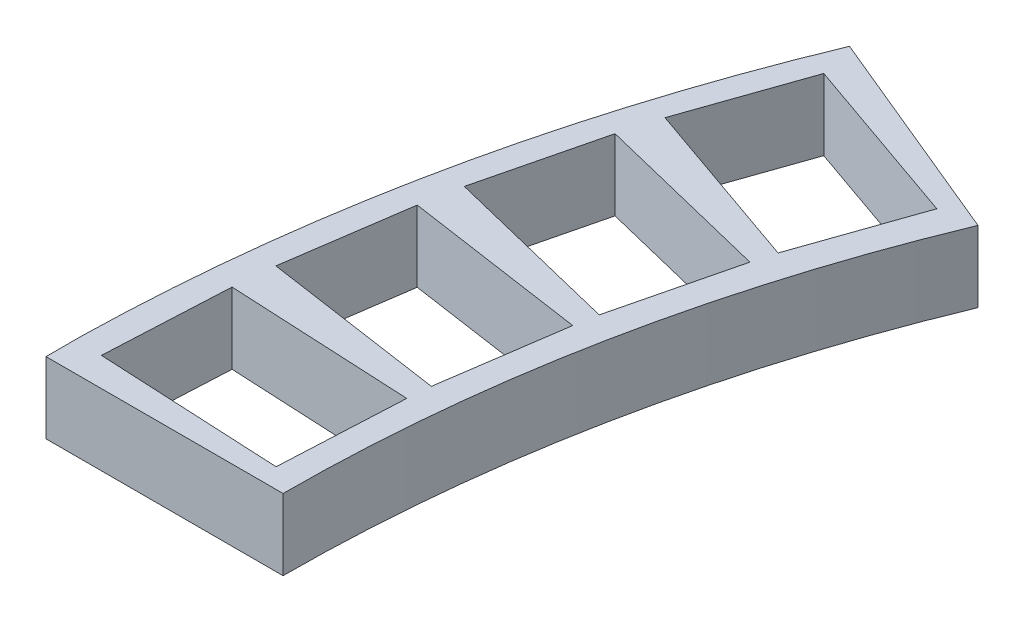
SolidWorks part; units mm, degrees
ref_plane "Front Plane" through (0, 0, 0) normal (0, 0, 1) x (1, 0, 0)
ref_plane "Top Plane" through (0, 0, 0) normal (0, 1, 0) x (1, 0, 0)
ref_plane "Right Plane" through (0, 0, 0) normal (1, 0, 0) x (0, 0, -1)
sketch "Sketch1" plane through (0, 0, 0) normal (0, 1, 0) x (1, 0, 0)
  line L0 (0, -1585.8629) -> (0, 77707.2829) construction
  line L1 (-1585.8629, 0) -> (77707.2829, 0) construction
  line L3 (-272.7199, 112.9643) -> (-235.7647, 97.6569)
  line L38 (-235.7647, 97.6569) -> (0, 0) construction
  line L58 (-295.1278, 6.0543) -> (-295.1278, 0)
  line L64 (-295.1278, 0) -> (-255.1898, 0)
  line L66 (-249.615, 73.0843) -> (-254.6156, 52.6884)
  line L67 (-254.6156, 52.6884) -> (-284.7239, 60.0701)
  line L91 (-241.6583, 96.6151) -> (-248.5803, 76.7888)
  line L92 (-248.5803, 76.7888) -> (-277.8479, 87.007)
  line L93 (-277.8479, 87.007) -> (-270.9258, 106.8334)
  line L94 (-270.9258, 106.8334) -> (-241.6583, 96.6151)
  line L95 (-284.7239, 60.0701) -> (-279.7233, 80.4661)
  line L96 (-279.7233, 80.4661) -> (-249.615, 73.0843)
  line L97 (-255.2924, 48.9021) -> (-258.3259, 28.1224)
  line L98 (-258.3259, 28.1224) -> (-289.0008, 32.6005)
  line L99 (-289.0008, 32.6005) -> (-285.9672, 53.3803)
  line L100 (-285.9672, 53.3803) -> (-255.2924, 48.9021)
  line L101 (-258.6388, 24.2889) -> (-259.6777, 3.3146)
  line L102 (-259.6777, 3.3146) -> (-290.6397, 4.8483)
  line L103 (-290.6397, 4.8483) -> (-289.6008, 25.8226)
  line L104 (-289.6008, 25.8226) -> (-258.6388, 24.2889)
  arc A1 (-295.1278, 6.0543) -> (-272.7199, 112.9643) centre (0, 0) cw
  arc A3 (-235.7647, 97.6569) -> (-255.1898, 0) centre (0, 0) ccw
  arc A59 (-202.2632, 163.0099) -> (-214.7699, 146.1385) centre (0, 0) ccw construction
  arc A60 (-202.2632, 163.0099) -> (-214.7699, 146.1385) centre (0, 0) ccw construction
  arc A61 (-202.2632, 163.0099) -> (-214.7699, 146.1385) centre (0, 0) ccw construction
  arc A62 (-202.2632, 163.0099) -> (-214.7699, 146.1385) centre (0, 0) ccw construction
  point P13 (0, 0)
  point P15 (-258.6388, 24.2889)
  point P34 (-258.3259, 28.1224)
  point P35 (-258.6388, 24.2889)
  point P36 (-258.3259, 28.1224)
  dimension "D1" = 22.5
  dimension "D7" = 4
extrude "Boss-Extrude1" add sketch "Sketch1" along normal blind 12
